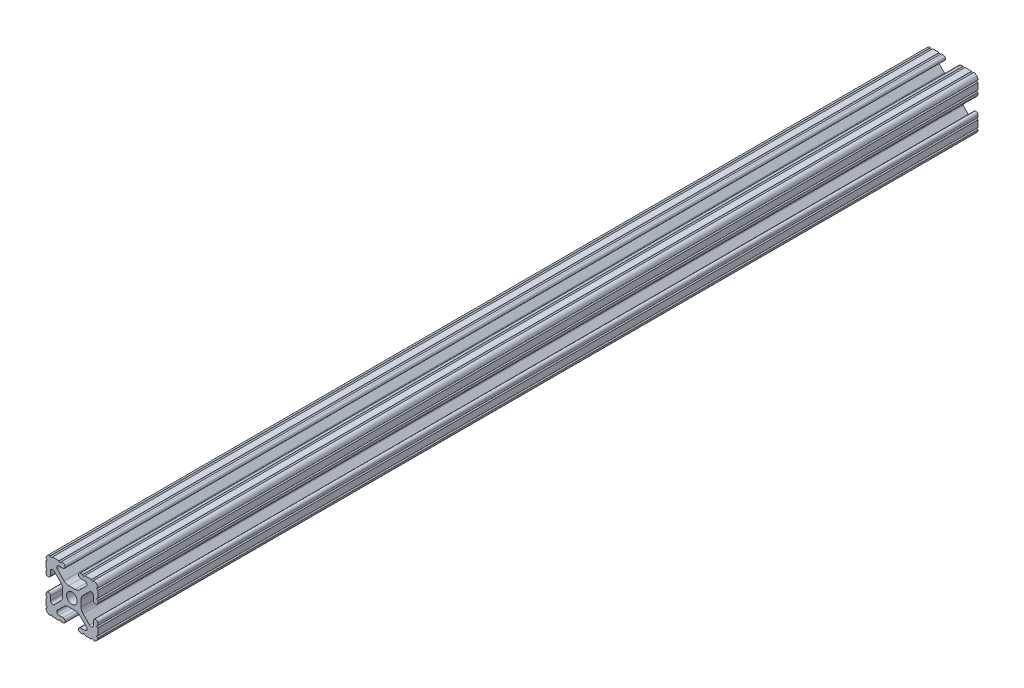
SolidWorks part; units mm, degrees
material "6105-T5 Aluminum"
ref_plane "Front Plane" through (0, 0, 0) normal (0, 0, 1) x (1, 0, 0)
ref_plane "Top Plane" through (0, 0, 0) normal (0, 1, 0) x (1, 0, 0)
ref_plane "Right Plane" through (0, 0, 0) normal (1, 0, 0) x (0, 0, -1)
sketch "Sketch1" plane through (0, 0, 0) normal (0, 0, 1) x (1, 0, 0)
  line L0 (12.7, 2.6035) -> (12.7, -2.6035) construction
  line L1 (2.1336, -12.7) -> (2.1082, -12.7)
  line L2 (6.3754, -12.7) -> (3.1496, -12.7)
  line L3 (8.3439, -12.7) -> (7.3914, -12.7)
  line L4 (6.3299, -10.4902) -> (8.3439, -10.4902)
  line L5 (8.8154, -5.4471) -> (5.5808, -8.6817)
  line L6 (5.5808, 8.6817) -> (8.8154, 5.4471)
  line L7 (8.3439, 10.4902) -> (6.3299, 10.4902)
  line L8 (25.4, -10.5918) -> (25.4, -10.5664)
  line L9 (25.4, -9.5504) -> (25.4, -6.3246)
  line L10 (25.4, -5.3086) -> (25.4, -4.3561)
  line L11 (23.1902, -4.3561) -> (23.1902, -6.3701)
  line L12 (21.3817, -7.1192) -> (18.1471, -3.8846)
  line L13 (17.2172, -1.6396) -> (17.2172, 1.6396)
  line L14 (18.1471, 3.8846) -> (21.3817, 7.1192)
  line L15 (23.1902, 6.3701) -> (23.1902, 4.3561)
  line L16 (25.4, 4.3561) -> (25.4, 5.3086)
  line L17 (25.4, 6.3246) -> (25.4, 9.5504)
  line L18 (25.4, 10.5664) -> (25.4, 10.5918)
  line L19 (23.2918, 12.7) -> (23.2664, 12.7)
  line L20 (22.2504, 12.7) -> (19.0246, 12.7)
  line L21 (18.0086, 12.7) -> (17.0561, 12.7)
  line L22 (17.0561, 10.4902) -> (19.0701, 10.4902)
  line L23 (19.8192, 8.6817) -> (16.5846, 5.4471)
  line L24 (14.3396, 4.5172) -> (11.0604, 4.5172)
  line L25 (7.3914, 12.7) -> (8.3439, 12.7)
  line L26 (3.1496, 12.7) -> (6.3754, 12.7)
  line L27 (2.1082, 12.7) -> (2.1336, 12.7)
  line L28 (0, 10.5664) -> (0, 10.5918)
  line L29 (0, 6.3246) -> (0, 9.5504)
  line L30 (0, 4.3561) -> (0, 5.3086)
  line L31 (2.2098, 6.3701) -> (2.2098, 4.3561)
  line L32 (7.2529, 3.8846) -> (4.0183, 7.1192)
  line L33 (8.1828, -1.6396) -> (8.1828, 1.6396)
  line L34 (4.0183, -7.1192) -> (7.2529, -3.8846)
  line L35 (2.2098, -4.3561) -> (2.2098, -6.3701)
  line L36 (0, -5.3086) -> (0, -4.3561)
  line L37 (0, -9.5504) -> (0, -6.3246)
  line L38 (0, -10.5918) -> (0, -10.5664)
  line L66 (11.0604, -4.5172) -> (14.3396, -4.5172)
  line L67 (16.5846, -5.4471) -> (19.8192, -8.6817)
  line L68 (19.0701, -10.4902) -> (17.0561, -10.4902)
  line L69 (17.0561, -12.7) -> (18.0086, -12.7)
  line L70 (19.0246, -12.7) -> (22.2504, -12.7)
  line L71 (23.2664, -12.7) -> (23.2918, -12.7)
  arc A0 (2.1336, -12.7) -> (3.1496, -12.7) centre (2.6416, -12.7) cw
  circle A1 centre (12.7, 0) radius 2.6035
  arc A2 (6.3754, -12.7) -> (7.3914, -12.7) centre (6.8834, -12.7) cw
  arc A3 (8.3439, -10.4902) -> (8.3439, -12.7) centre (8.3439, -11.5951) cw
  arc A4 (6.3299, -10.4902) -> (5.5808, -8.6817) centre (6.3299, -9.4308) cw
  arc A5 (8.8154, -5.4471) -> (11.0604, -4.5172) centre (11.0604, -7.6922) cw
  arc A6 (11.0604, 4.5172) -> (8.8154, 5.4471) centre (11.0604, 7.6922) cw
  arc A7 (5.5808, 8.6817) -> (6.3299, 10.4902) centre (6.3299, 9.4308) cw
  arc A8 (8.3439, 12.7) -> (8.3439, 10.4902) centre (8.3439, 11.5951) cw
  arc A9 (7.3914, 12.7) -> (6.3754, 12.7) centre (6.8834, 12.7) cw
  arc A10 (23.2918, -12.7) -> (25.4, -10.5918) centre (23.2918, -10.5918) ccw
  arc A11 (25.4, -9.5504) -> (25.4, -10.5664) centre (25.4, -10.0584) ccw
  arc A12 (25.4, -5.3086) -> (25.4, -6.3246) centre (25.4, -5.8166) ccw
  arc A13 (25.4, -4.3561) -> (23.1902, -4.3561) centre (24.2951, -4.3561) ccw
  arc A14 (21.3817, -7.1192) -> (23.1902, -6.3701) centre (22.1308, -6.3701) ccw
  arc A15 (17.2172, -1.6396) -> (18.1471, -3.8846) centre (20.3922, -1.6396) ccw
  arc A16 (18.1471, 3.8846) -> (17.2172, 1.6396) centre (20.3922, 1.6396) ccw
  arc A17 (23.1902, 6.3701) -> (21.3817, 7.1192) centre (22.1308, 6.3701) ccw
  arc A18 (23.1902, 4.3561) -> (25.4, 4.3561) centre (24.2951, 4.3561) ccw
  arc A19 (25.4, 6.3246) -> (25.4, 5.3086) centre (25.4, 5.8166) ccw
  arc A20 (25.4, 10.5664) -> (25.4, 9.5504) centre (25.4, 10.0584) ccw
  arc A21 (25.4, 10.5918) -> (23.2918, 12.7) centre (23.2918, 10.5918) ccw
  arc A22 (22.2504, 12.7) -> (23.2664, 12.7) centre (22.7584, 12.7) ccw
  arc A23 (18.0086, 12.7) -> (19.0246, 12.7) centre (18.5166, 12.7) ccw
  arc A24 (17.0561, 12.7) -> (17.0561, 10.4902) centre (17.0561, 11.5951) ccw
  arc A25 (19.8192, 8.6817) -> (19.0701, 10.4902) centre (19.0701, 9.4308) ccw
  arc A26 (14.3396, 4.5172) -> (16.5846, 5.4471) centre (14.3396, 7.6922) ccw
  arc A27 (3.1496, 12.7) -> (2.1336, 12.7) centre (2.6416, 12.7) cw
  arc A28 (0, 10.5918) -> (2.1082, 12.7) centre (2.1082, 10.5918) cw
  arc A29 (0, 10.5664) -> (0, 9.5504) centre (0, 10.0584) cw
  arc A30 (0, 6.3246) -> (0, 5.3086) centre (0, 5.8166) cw
  arc A31 (2.2098, 4.3561) -> (0, 4.3561) centre (1.1049, 4.3561) cw
  arc A32 (2.2098, 6.3701) -> (4.0183, 7.1192) centre (3.2692, 6.3701) cw
  arc A33 (7.2529, 3.8846) -> (8.1828, 1.6396) centre (5.0078, 1.6396) cw
  arc A34 (8.1828, -1.6396) -> (7.2529, -3.8846) centre (5.0078, -1.6396) cw
  arc A35 (4.0183, -7.1192) -> (2.2098, -6.3701) centre (3.2692, -6.3701) cw
  arc A36 (0, -4.3561) -> (2.2098, -4.3561) centre (1.1049, -4.3561) cw
  arc A37 (0, -5.3086) -> (0, -6.3246) centre (0, -5.8166) cw
  arc A38 (0, -9.5504) -> (0, -10.5664) centre (0, -10.0584) cw
  arc A39 (2.1082, -12.7) -> (0, -10.5918) centre (2.1082, -10.5918) cw
  arc A69 (16.5846, -5.4471) -> (14.3396, -4.5172) centre (14.3396, -7.6922) ccw
  arc A70 (19.0701, -10.4902) -> (19.8192, -8.6817) centre (19.0701, -9.4308) ccw
  arc A71 (17.0561, -10.4902) -> (17.0561, -12.7) centre (17.0561, -11.5951) ccw
  arc A72 (19.0246, -12.7) -> (18.0086, -12.7) centre (18.5166, -12.7) ccw
  arc A73 (23.2664, -12.7) -> (22.2504, -12.7) centre (22.7584, -12.7) ccw
extrude "Extrude1" add sketch "Sketch1" against normal blind 431.8
